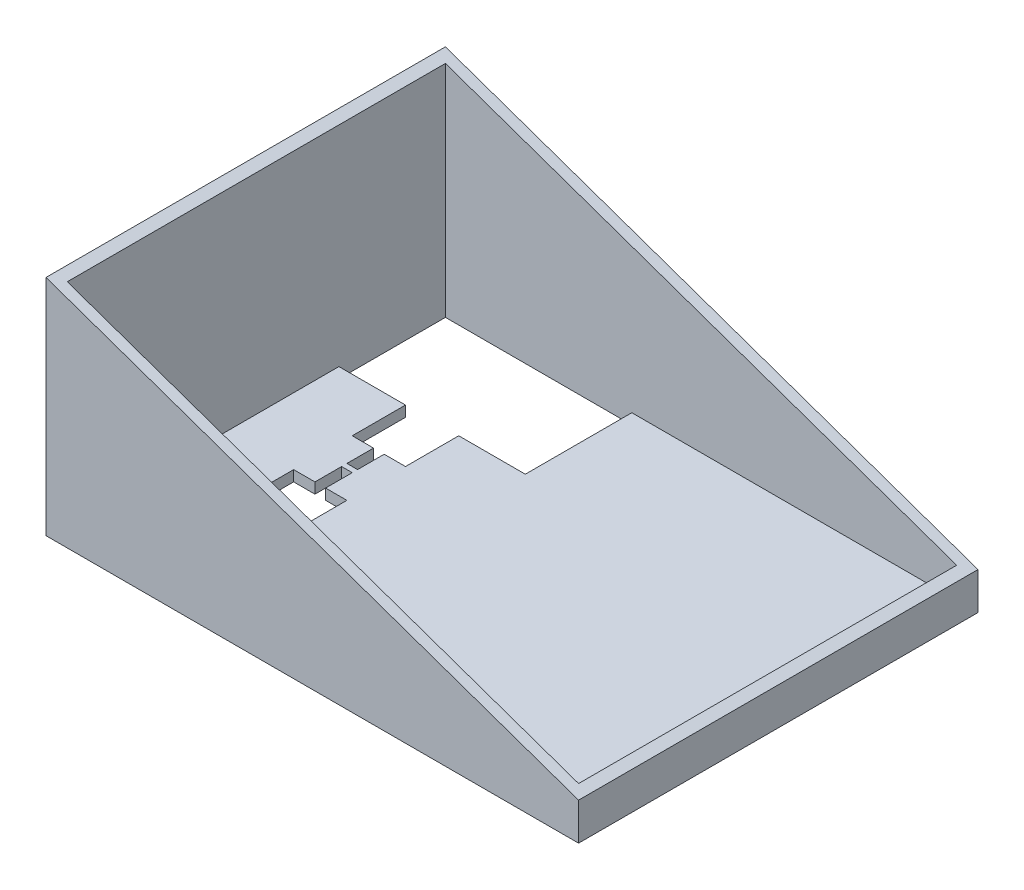
SolidWorks part; units mm, degrees
ref_plane "Front Plane" through (0, 0, 0) normal (0, 0, 1) x (1, 0, 0)
ref_plane "Top Plane" through (0, 0, 0) normal (0, 1, 0) x (1, 0, 0)
ref_plane "Right Plane" through (0, 0, 0) normal (1, 0, 0) x (0, 0, -1)
sketch "Sketch1" plane through (0, 0, 0) normal (0, 1, 0) x (1, 0, 0)
  line L0 (-196, 75) -> (-4, 75) construction
  line L1 (0, 0) -> (-200, 0)
  line L2 (0, 0) -> (0, 150)
  line L3 (0, 150) -> (-200, 150)
  line L4 (-200, 0) -> (-200, 150)
  line L5 (-196, 146) -> (-4, 146)
  line L6 (-196, 146) -> (-196, 4)
  line L7 (-196, 4) -> (-4, 4)
  line L8 (-4, 146) -> (-4, 4)
  line L9 (-196, 146) -> (-126, 146)
  line L10 (-196, 146) -> (-196, 106)
  line L11 (-196, 106) -> (-126, 106)
  line L12 (-126, 146) -> (-126, 106)
  line L13 (-196, 44) -> (-126, 44)
  line L14 (-126, 4) -> (-126, 44)
  line L15 (-196, 4) -> (-126, 4)
  line L16 (-196, 4) -> (-196, 44)
  line L17 (-171, 64) -> (-151, 64)
  line L18 (-171, 106) -> (-151, 106)
  line L19 (-171, 106) -> (-171, 86)
  line L20 (-171, 86) -> (-151, 86)
  line L21 (-151, 106) -> (-151, 86)
  line L22 (-151, 44) -> (-151, 64)
  line L23 (-171, 44) -> (-151, 44)
  line L24 (-171, 44) -> (-171, 64)
  line L25 (-163, 76) -> (-159, 76)
  line L26 (-163, 64) -> (-159, 64)
  line L27 (-163, 64) -> (-163, 74)
  line L28 (-163, 74) -> (-159, 74)
  line L29 (-159, 64) -> (-159, 74)
  line L30 (-159, 86) -> (-159, 76)
  line L31 (-163, 86) -> (-159, 86)
  line L32 (-163, 86) -> (-163, 76)
  dimension "D1" = 200
  dimension "D2" = 150
  dimension "D3" = 192
  dimension "D4" = 142
  dimension "D5" = 4
  dimension "D6" = 4
  dimension "D7" = 40
  dimension "D8" = 70
  dimension "D9" = 20
  dimension "D10" = 20
  dimension "D11" = 25
  dimension "D12" = 4
  dimension "D13" = 10
  dimension "D14" = 8
extrude "Boss-Extrude2" add sketch "Sketch1" along normal blind 4 contours L4 L1 L2 L3 L5 L8 L7 L6 | L0 L6 L13 L24 L17 L27 L28 L29 L22 L14 L7 L8 | L6 L0 L8 L5 L12 L11 L21 L20 L30 L25 L32 L19
sketch "Sketch2" plane through (0, 4, 0) normal (0, 1, 0) x (1, 0, 0)
  line L1 (-200, 0) -> (0, 0)
  line L2 (-200, 0) -> (-200, 150)
  line L3 (-200, 150) -> (0, 150)
  line L4 (0, 0) -> (0, 150)
  line L5 (-196, 146) -> (-4, 146)
  line L6 (-196, 146) -> (-196, 4)
  line L7 (-196, 4) -> (-4, 4)
  line L8 (-4, 146) -> (-4, 4)
  dimension "D1" = 4
  dimension "D2" = 4
extrude "Boss-Extrude3" add sketch "Sketch2" along normal blind 80
sketch "Sketch3" plane through (0, 0, 0) normal (0, 0, 1) x (1, 0, 0)
  line L0 (-200, 84) -> (0, 14)
  line L1 (0, 84) -> (0, 0) construction
  line L2 (0, 14) -> (0, 84)
  line L3 (0, 84) -> (-200, 84)
  dimension "D1" = 70
extrude "Cut-Extrude1" cut sketch "Sketch3" against normal blind 150
sketch "Sketch4" plane through (0, 4, 0) normal (0, 1, 0) x (1, 0, 0)
  line L6 (-4, 146) -> (-4, 4) construction
  line L7 (-4, 146) -> (-196, 146) construction
  line L17 (-4, 4) -> (-4, 146) construction
  line L18 (-13.5, 28.5) -> (-19.5, 28.5)
  line L19 (-13.5, 28.5) -> (-13.5, 38.5)
  line L20 (-13.5, 38.5) -> (-19.5, 38.5)
  line L21 (-19.5, 28.5) -> (-19.5, 38.5)
  line L22 (-196, 75) -> (-4, 75) construction
  line L23 (-196, 106) -> (-196, 44) construction
  line L24 (-13.5, 111.5) -> (-19.5, 111.5)
  line L25 (-19.5, 121.5) -> (-19.5, 111.5)
  line L26 (-13.5, 121.5) -> (-19.5, 121.5)
  line L27 (-13.5, 121.5) -> (-13.5, 111.5)
  line L28 (-19.5, 95.5) -> (-25.5, 95.5)
  line L29 (-19.5, 44.5) -> (-25.5, 44.5)
  line L30 (-19.5, 44.5) -> (-19.5, 54.5)
  line L31 (-19.5, 54.5) -> (-25.5, 54.5)
  line L32 (-25.5, 44.5) -> (-25.5, 54.5)
  line L33 (-25.5, 105.5) -> (-25.5, 95.5)
  line L34 (-19.5, 105.5) -> (-25.5, 105.5)
  line L35 (-19.5, 105.5) -> (-19.5, 95.5)
  line L36 (-25.5, 70.5) -> (-31.5, 70.5)
  line L37 (-25.5, 89.5) -> (-31.5, 89.5)
  line L38 (-25.5, 89.5) -> (-25.5, 79.5)
  line L39 (-25.5, 79.5) -> (-31.5, 79.5)
  line L40 (-31.5, 89.5) -> (-31.5, 79.5)
  line L41 (-31.5, 60.5) -> (-31.5, 70.5)
  line L42 (-25.5, 60.5) -> (-31.5, 60.5)
  line L43 (-25.5, 60.5) -> (-25.5, 70.5)
  line L44 (-25.5, 127.5) -> (-31.5, 127.5)
  line L45 (-25.5, 127.5) -> (-25.5, 137.5)
  line L46 (-25.5, 137.5) -> (-31.5, 137.5)
  line L47 (-31.5, 127.5) -> (-31.5, 137.5)
  line L48 (-25.5, 12.5) -> (-31.5, 12.5)
  line L49 (-31.5, 22.5) -> (-31.5, 12.5)
  line L50 (-25.5, 22.5) -> (-31.5, 22.5)
  line L51 (-25.5, 22.5) -> (-25.5, 12.5)
  circle A0 centre (-48.5, 132.5) radius 3
  circle A1 centre (-48.5, 17.5) radius 3
  point P44 (0, 0)
  dimension "D8" = 17
  dimension "D11" = 6
  dimension "D20" = 13.5
  dimension "D2" = 24.5
  dimension "D3" = 10
  dimension "D4" = 10
  dimension "D5" = 6
  dimension "D6" = 6
  dimension "D7" = 21.5
  dimension "D9" = 6
  dimension "D10" = 9.5
  dimension "D12" = 10
  dimension "D13" = 6
  dimension "D14" = 15.5
  dimension "D15" = 6
  dimension "D16" = 6
  dimension "D17" = 10
  dimension "D18" = 6
  dimension "D19" = 21.5
